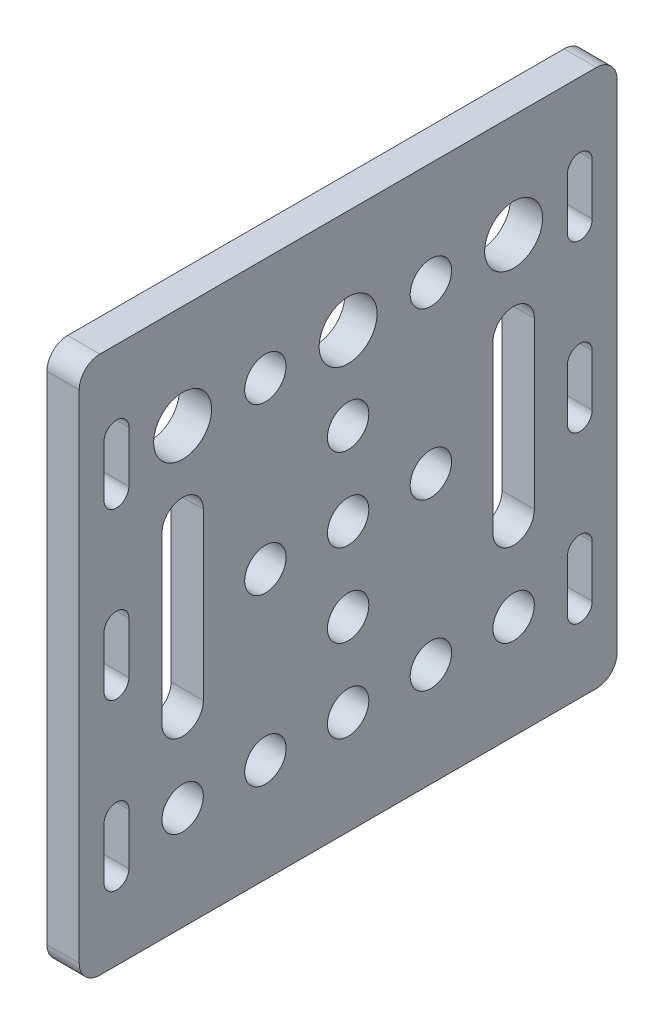
SolidWorks part; units mm, degrees
ref_plane "Front Plane" through (0, 0, 0) normal (0, 0, 1) x (1, 0, 0)
ref_plane "Top Plane" through (0, 0, 0) normal (0, 1, 0) x (1, 0, 0)
ref_plane "Right Plane" through (0, 0, 0) normal (1, 0, 0) x (0, 0, -1)
sketch "Sketch1" plane through (0, 0, 0) normal (1, 0, 0) x (0, 0, -1)
  line L0 (30, 32.5) -> (-30, 32.5)
  line L1 (-32.5, 30) -> (-32.5, -30)
  line L2 (-30, -32.5) -> (30, -32.5)
  line L3 (32.5, -30) -> (32.5, 30)
  line L4 (28, 16.9) -> (28, 23.1) construction
  line L5 (26.5, 16.9) -> (26.5, 23.1)
  line L6 (29.5, 16.9) -> (29.5, 23.1)
  line L7 (28, -3.1) -> (28, 3.1) construction
  line L8 (26.5, -3.1) -> (26.5, 3.1)
  line L9 (29.5, -3.1) -> (29.5, 3.1)
  line L10 (28, -23.1) -> (28, -16.9) construction
  line L11 (26.5, -23.1) -> (26.5, -16.9)
  line L12 (29.5, -23.1) -> (29.5, -16.9)
  line L13 (-28, -23.1) -> (-28, -16.9) construction
  line L14 (-29.5, -23.1) -> (-29.5, -16.9)
  line L15 (-26.5, -23.1) -> (-26.5, -16.9)
  line L16 (20, -10) -> (20, 10) construction
  line L17 (17.5, -10) -> (17.5, 10)
  line L18 (22.5, -10) -> (22.5, 10)
  line L19 (-20, -10) -> (-20, 10) construction
  line L20 (-22.5, -10) -> (-22.5, 10)
  line L21 (-17.5, -10) -> (-17.5, 10)
  line L22 (-28, 16.9) -> (-28, 23.1) construction
  line L23 (-29.5, 16.9) -> (-29.5, 23.1)
  line L24 (-26.5, 16.9) -> (-26.5, 23.1)
  line L25 (-28, -3.1) -> (-28, 3.1) construction
  line L26 (-29.5, -3.1) -> (-29.5, 3.1)
  line L27 (-26.5, -3.1) -> (-26.5, 3.1)
  line L28 (-10, 20) -> (-20, 20) construction
  line L30 (10, 20) -> (20, 20) construction
  line L31 (10, -20) -> (20, -20) construction
  line L32 (-10, -20) -> (-20, -20) construction
  arc A0 (30, -32.5) -> (32.5, -30) centre (30, -30) ccw
  arc A1 (32.5, 30) -> (30, 32.5) centre (30, 30) ccw
  arc A2 (-30, 32.5) -> (-32.5, 30) centre (-30, 30) ccw
  arc A3 (-32.5, -30) -> (-30, -32.5) centre (-30, -30) ccw
  circle A4 centre (0, -20) radius 2.5
  circle A5 centre (10, -20) radius 2.5
  circle A6 centre (-10, -20) radius 2.5
  circle A7 centre (10, 0) radius 2.5
  circle A8 centre (0, -10) radius 2.5
  circle A9 centre (-10, 0) radius 2.5
  circle A10 centre (0, 0) radius 2.5
  circle A11 centre (0, 10) radius 2.5
  circle A12 centre (20, -20) radius 2.5
  circle A13 centre (-20, -20) radius 2.5
  circle A14 centre (10, 20) radius 2.5
  circle A15 centre (0, 20) radius 3.5
  circle A16 centre (-10, 20) radius 2.5
  circle A17 centre (20, 20) radius 3.5
  circle A18 centre (-20, 20) radius 3.5
  arc A19 (26.5, 16.9) -> (29.5, 16.9) centre (28, 16.9) ccw
  arc A20 (29.5, 23.1) -> (26.5, 23.1) centre (28, 23.1) ccw
  arc A21 (26.5, -3.1) -> (29.5, -3.1) centre (28, -3.1) ccw
  arc A22 (29.5, 3.1) -> (26.5, 3.1) centre (28, 3.1) ccw
  arc A23 (26.5, -23.1) -> (29.5, -23.1) centre (28, -23.1) ccw
  arc A24 (29.5, -16.9) -> (26.5, -16.9) centre (28, -16.9) ccw
  arc A25 (-29.5, -23.1) -> (-26.5, -23.1) centre (-28, -23.1) ccw
  arc A26 (-26.5, -16.9) -> (-29.5, -16.9) centre (-28, -16.9) ccw
  arc A27 (17.5, -10) -> (22.5, -10) centre (20, -10) ccw
  arc A28 (22.5, 10) -> (17.5, 10) centre (20, 10) ccw
  arc A29 (-22.5, -10) -> (-17.5, -10) centre (-20, -10) ccw
  arc A30 (-17.5, 10) -> (-22.5, 10) centre (-20, 10) ccw
  arc A31 (-29.5, 16.9) -> (-26.5, 16.9) centre (-28, 16.9) ccw
  arc A32 (-26.5, 23.1) -> (-29.5, 23.1) centre (-28, 23.1) ccw
  arc A33 (-29.5, -3.1) -> (-26.5, -3.1) centre (-28, -3.1) ccw
  arc A34 (-26.5, 3.1) -> (-29.5, 3.1) centre (-28, 3.1) ccw
  circle A35 centre (0, 0) radius 2.5 construction
  circle A36 centre (0, -10) radius 2.5 construction
  circle A37 centre (0, -20) radius 2.5 construction
  circle A38 centre (10, 20) radius 2.5 construction
  circle A39 centre (10, 0) radius 2.5 construction
  circle A40 centre (10, -20) radius 2.5 construction
  arc A41 (29.5, -16.9) -> (26.5, -16.9) centre (28, -16.9) ccw construction
  arc A42 (29.5, 3.1) -> (26.5, 3.1) centre (28, 3.1) ccw construction
  circle A44 centre (0, 20) radius 3.5 construction
  circle A45 centre (0, 10) radius 2.5 construction
  circle A46 centre (-10, 20) radius 2.5 construction
  circle A47 centre (-10, 0) radius 2.5 construction
  circle A48 centre (-10, -20) radius 2.5 construction
  point P65 (28, 20)
  point P70 (28, 0)
  point P79 (28, -20)
  point P88 (-28, -20)
  point P97 (20, 0)
  point P106 (-20, 0)
  point P115 (-28, 20)
  point P124 (-28, 0)
  dimension "D1" = 20
  dimension "D2" = 20
extrude "Boss-Extrude1" add sketch "Sketch1" against normal blind 3.9
